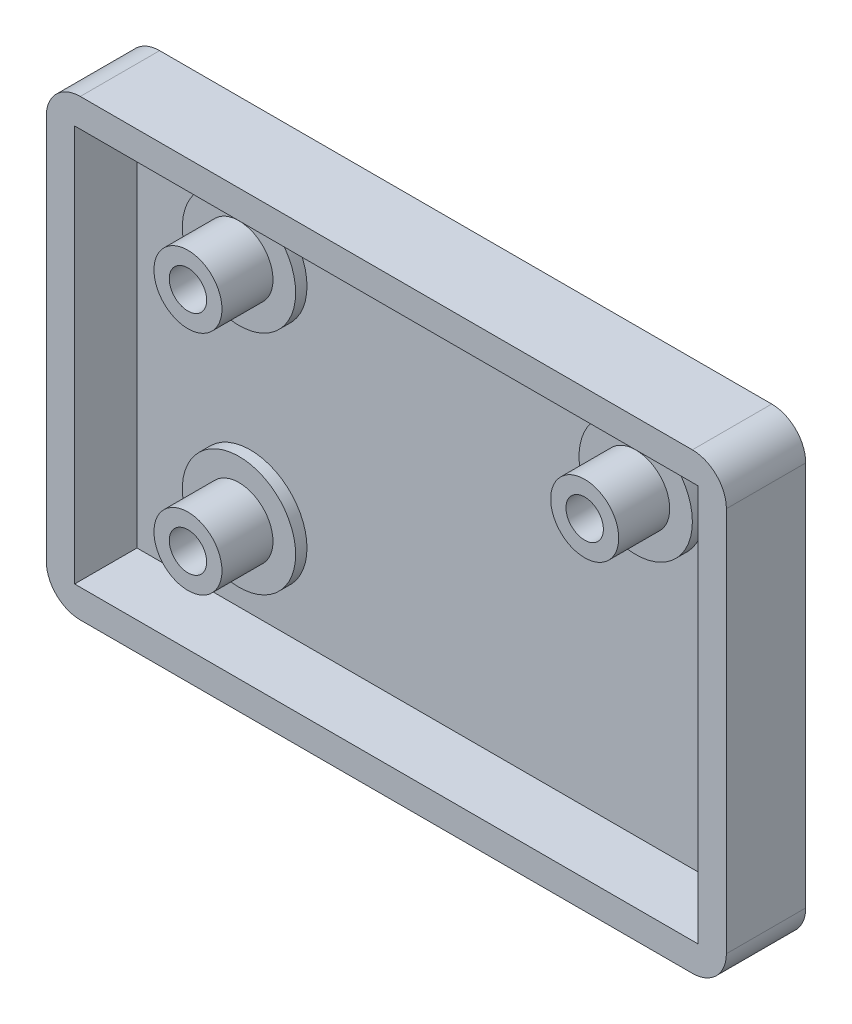
SolidWorks part; units mm, degrees
ref_plane "Alzado" through (0, 0, 0) normal (0, 0, 1) x (1, 0, 0)
ref_plane "Planta" through (0, 0, 0) normal (0, 1, 0) x (1, 0, 0)
ref_plane "Vista lateral" through (0, 0, 0) normal (1, 0, 0) x (0, 0, -1)
sketch "Croquis1" plane through (0, 0, 0) normal (0, 0, 1) x (1, 0, 0)
  line L1 (30, -20) -> (-30, -20)
  line L2 (30, -20) -> (30, 20)
  line L3 (30, 20) -> (-30, 20)
  line L4 (-30, -20) -> (-30, 20)
  line L5 (30, -20) -> (-30, 20) construction
  line L6 (30, 20) -> (-30, -20) construction
  point P0 (0, 0)
  dimension "D1" = 40
  dimension "D2" = 60
extrude "Saliente-Extruir1" add sketch "Croquis1" along normal blind 7
sketch "Croquis2" plane through (0, 0, 7) normal (0, 0, 1) x (1, 0, 0)
  line L1 (27.5, -17.5) -> (-27.5, -17.5)
  line L2 (27.5, -17.5) -> (27.5, 17.5)
  line L3 (27.5, 17.5) -> (-27.5, 17.5)
  line L4 (-27.5, -17.5) -> (-27.5, 17.5)
  line L5 (27.5, -17.5) -> (-27.5, 17.5) construction
  line L6 (27.5, 17.5) -> (-27.5, -17.5) construction
  point P0 (0, 0)
  dimension "D1" = 35
  dimension "D2" = 55
extrude "Cortar-Extruir1" cut sketch "Croquis2" against normal blind 5.5
fillet "Redondeo1" radius 3 4 edges at (30, 20, 3.5) (30, -20, 3.5) (-30, -20, 3.5) (-30, 20, 3.5)
sketch "Croquis3" plane through (0, 0, 0) normal (0, 0, -1) x (-1, 0, 0)
  circle A0 centre (-17.5, 10) radius 1.65
  circle A2 centre (17.5, 10) radius 1.65
  circle A3 centre (17.5, -10) radius 1.65
  point P10 (0, 0)
  point P11 (0, 0)
  dimension "D1" = 3.3
  dimension "D2" = 3.3
  dimension "D3" = 3.3
  dimension "D6" = 20
  dimension "D7" = 35
  dimension "D10" = 10
  dimension "D11" = 17.5
  dimension "D12" = 17.5
extrude "Cortar-Extruir2" cut sketch "Croquis3" against normal blind 30.5
sketch "Croquis5" plane through (0, 0, 1.5) normal (0, 0, 1) x (1, 0, 0)
  circle A0 centre (-17.5, 10) radius 1.65
  circle A1 centre (-17.5, 10) radius 5
  circle A2 centre (17.5, 10) radius 1.65
  circle A3 centre (-17.5, -10) radius 1.65
  circle A5 centre (17.5, 10) radius 5
  circle A7 centre (-17.5, -10) radius 5
  dimension "D1" = 10
  dimension "D2" = 10
  dimension "D4" = 10
extrude "Saliente-Extruir2" add sketch "Croquis5" along normal blind 1
sketch "Croquis6" plane through (0, 0, 2.5) normal (0, 0, 1) x (1, 0, 0)
  circle A0 centre (-17.5, 10) radius 1.65
  circle A1 centre (17.5, 10) radius 1.65
  circle A3 centre (-17.5, -10) radius 1.65
  circle A4 centre (-17.5, 10) radius 3
  circle A5 centre (17.5, 10) radius 3
  circle A6 centre (-17.5, -10) radius 3
  dimension "D1" = 6
  dimension "D2" = 6
  dimension "D3" = 6
extrude "Saliente-Extruir3" add sketch "Croquis6" along normal blind 4.5
